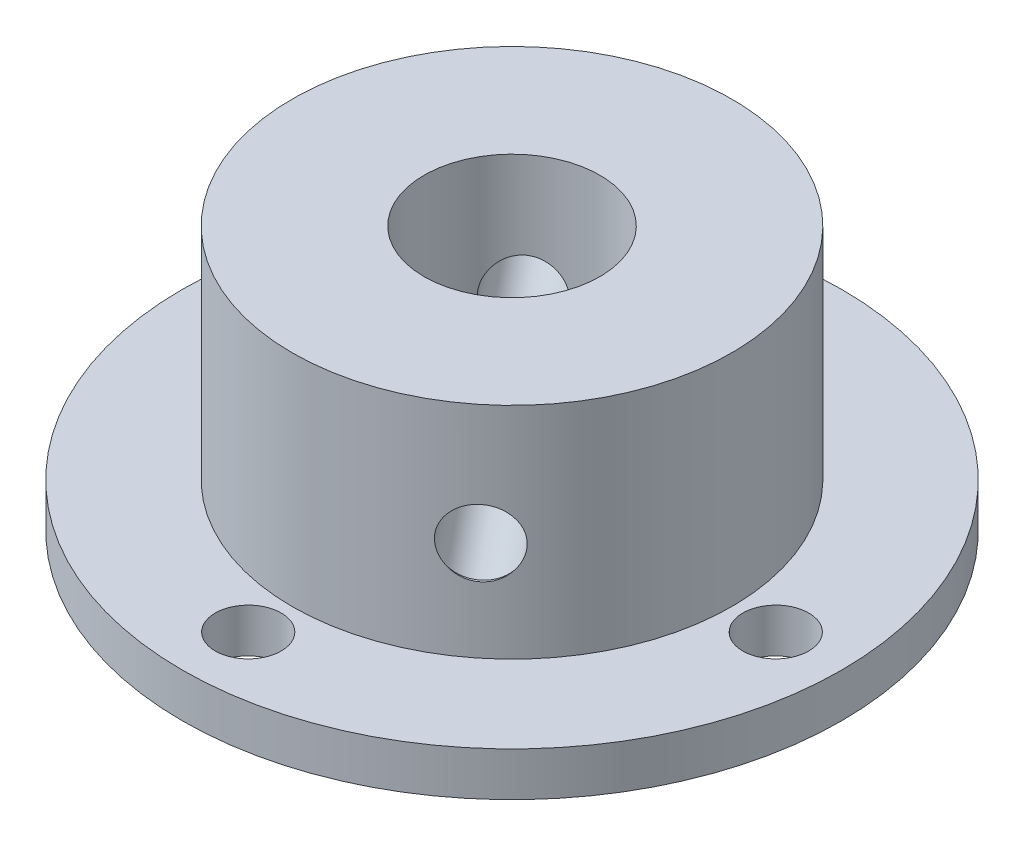
SolidWorks part; units mm, degrees
ref_plane "Front Plane" through (0, 0, 0) normal (0, 0, 1) x (1, 0, 0)
ref_plane "Top Plane" through (0, 0, 0) normal (0, 1, 0) x (1, 0, 0)
ref_plane "Right Plane" through (0, 0, 0) normal (1, 0, 0) x (0, 0, -1)
sketch "Sketch1" plane through (0, 0, 0) normal (0, 1, 0) x (1, 0, 0)
  circle A0 centre (0, 0) radius 15
  dimension "D1" = 30
extrude "Boss-Extrude1" add sketch "Sketch1" along normal blind 2
sketch "Sketch2" plane through (0, 2, 0) normal (0, 1, 0) x (1, 0, 0)
  circle A0 centre (0, 0) radius 10
  dimension "D1" = 20
extrude "Boss-Extrude2" add sketch "Sketch2" along normal blind 10
sketch "Sketch3" plane through (0, 12, 0) normal (0, 1, 0) x (1, 0, 0)
  circle A0 centre (0, 0) radius 4
  dimension "D1" = 8
extrude "Cut-Extrude1" cut sketch "Sketch3" against normal through all
sketch "Sketch4" plane through (0, 2, 0) normal (0, 1, 0) x (1, 0, 0)
  line L0 (0, 0) -> (-25.3532, 0) construction
  circle A0 centre (-12, 0) radius 1.5
  circle A1 centre (0, 12) radius 1.5
  circle A2 centre (12, 0) radius 1.5
  circle A3 centre (0, -12) radius 1.5
  point P14 (0, 0)
  dimension "D1" = 3
  dimension "D2" = 12
  dimension "D3" = 4
extrude "Cut-Extrude2" cut sketch "Sketch4" against normal blind 10
hole_wizard "Ø3.0 (3) Diameter Hole2" positions "3DSketch2" profile "Sketch6" hole size "Ø3.0" standard "ISO" end condition through all
sketch3d "3DSketch2"
  point P0 (6.3173, 6.5364, 7.7519)
sketch "Sketch6" plane through (6.3173, 6.5364, 7.7519) normal (0, 1, 0) x (0.7752, 0, -0.6317)
  line L0 (0, 0) -> (0, 31.1038)
  line L1 (0, 31.1038) -> (1.5, 31.1038)
  line L2 (1.5, 31.1038) -> (1.5, 0.0604)
  line L3 (1.5, 0.0604) -> (1.525, 0)
  line L5 (1.525, 0) -> (0, 0)
  line L6 (-1.5, 0.0604) -> (-1.525, 0) construction
  line L11 (0, -6.35) -> (0, 107.95) construction
  dimension "Thru Hole Dia." = 3
  dimension "Thru Hole Depth" = 31.1038
  dimension "Near C'Sink Dia." = 3.05
  dimension "Near C'Sink Angle" = 45
